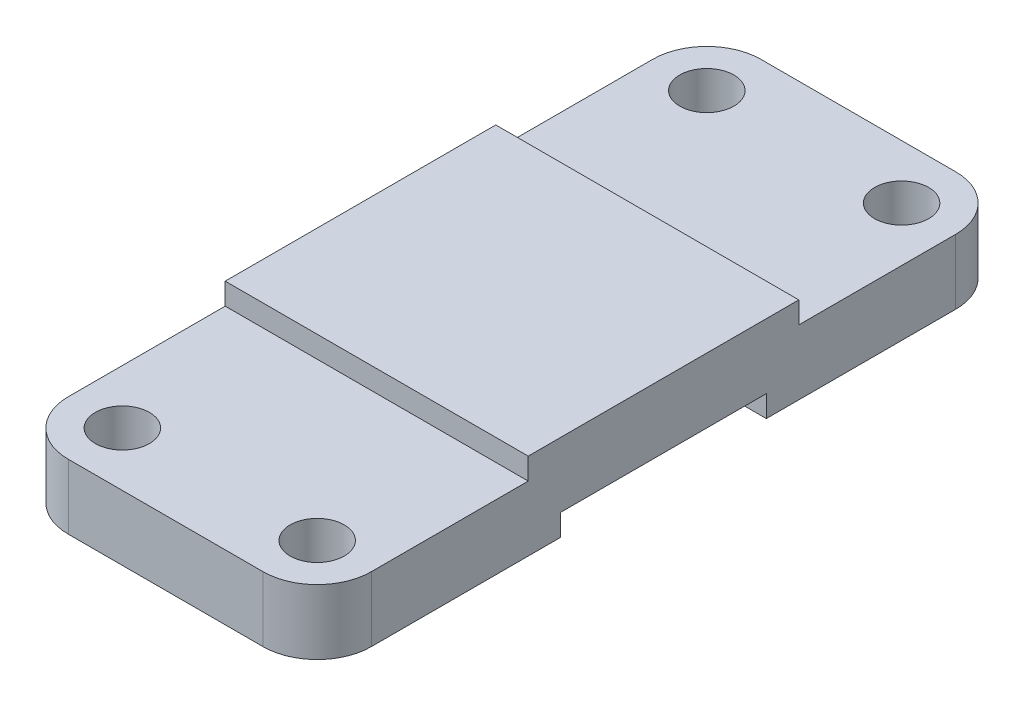
SolidWorks part; units mm, degrees
ref_plane "Ön Düzlem" through (0, 0, 0) normal (0, 0, 1) x (1, 0, 0)
ref_plane "Üst Düzlem" through (0, 0, 0) normal (0, 1, 0) x (1, 0, 0)
ref_plane "Sağ Düzlem" through (0, 0, 0) normal (1, 0, 0) x (0, 0, -1)
sketch "Sketch1" plane through (0, 0, 0) normal (1, 0, 0) x (0, 0, -1)
  line L0 (89, 12) -> (128, 12)
  line L9 (0, 0) -> (45, 0)
  line L10 (0, 0) -> (0, 12)
  line L11 (0, 12) -> (39, 12)
  line L12 (128, 0) -> (128, 12)
  line L14 (39, 12) -> (39, 16)
  line L15 (39, 16) -> (89, 16)
  line L16 (89, 12) -> (89, 16)
  line L17 (83, 0) -> (128, 0)
  line L19 (45, 0) -> (45, 4)
  line L20 (45, 4) -> (83, 4)
  line L21 (83, 0) -> (83, 4)
  point P9 (64, 16)
  point P16 (64, 4)
  dimension "D1" = 128
  dimension "D2" = 12
  dimension "D3" = 4
  dimension "D4" = 50
  dimension "D5" = 4
  dimension "D6" = 38
extrude "Boss-Extrude1" add sketch "Sketch1" against normal blind 56
fillet "Fillet1" radius 10 4 edges at (-56, 6, -128) (0, 6, -128) (-56, 6, 0) (0, 6, 0)
sketch "Sketch2" plane through (0, 12, 0) normal (0, 1, 0) x (1, 0, 0)
  circle A0 centre (-46, 118) radius 5
  circle A1 centre (-10, 118) radius 5
  circle A2 centre (-10, 10) radius 5
  circle A3 centre (-46, 10) radius 5
  dimension "D1" = 10
extrude "Cut-Extrude1" cut sketch "Sketch2" against normal through all
